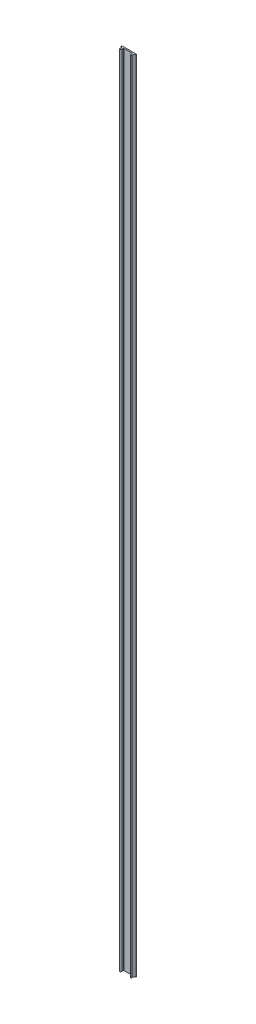
SolidWorks part; units mm, degrees
ref_plane "Top" through (0, 0, 0) normal (0, 0, 1) x (1, 0, 0)
ref_plane "Front" through (0, 0, 0) normal (0, 1, 0) x (1, 0, 0)
ref_plane "Right" through (0, 0, 0) normal (1, 0, 0) x (0, 0, -1)
sketch "Profile Sketch" plane through (0, 0, 0) normal (0, 1, 0) x (1, 0, 0)
  line L0 (0, 0.762) -> (4.2358, 0.762)
  line L1 (0, 0) -> (2.4324, 0)
  line L2 (2.8896, -0.4572) -> (2.8896, -1.3613)
  line L3 (0, 0) -> (0, 0.762)
  arc A0 (4.693, 0.3048) -> (4.2358, 0.762) centre (4.2358, 0.3048) ccw
  arc A1 (4.693, 0.3048) -> (3.7489, -1.2016) centre (4.7859, -0.8025) ccw
  arc A2 (3.7489, -1.2016) -> (2.8896, -1.3613) centre (3.3341, -1.3613) cw
  arc A3 (2.8896, -0.4572) -> (2.4324, 0) centre (2.4324, -0.4572) ccw
  dimension "D4" = 0.4572
  dimension "D5" = 0.4445
  dimension "D6" = 1.1111
  dimension "D7" = 0.4572
  dimension "D1" = 0.762
  dimension "D2" = 4.2358
  dimension "D3" = 2.8896
  dimension "D8" = 1.3613
  dimension "D9" = 0.4572
extrude "Profile Extrude" add sketch "Profile Sketch" along normal blind 500
mirror "Profile Mirror" about plane through (0, 0, 0) normal (1, 0, 0) of "Profile Extrude"
